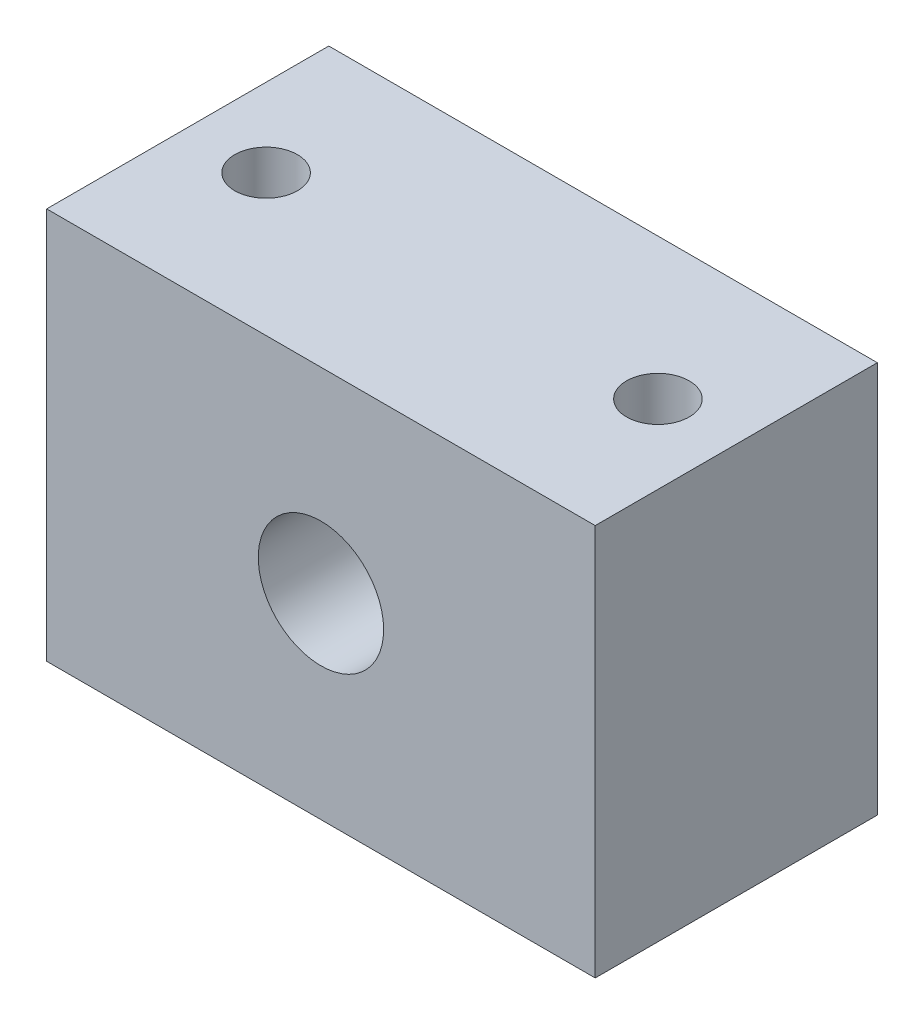
SolidWorks part; units mm, degrees
ref_plane "Front Plane" through (0, 0, 0) normal (0, 0, 1) x (1, 0, 0)
ref_plane "Top Plane" through (0, 0, 0) normal (0, 1, 0) x (1, 0, 0)
ref_plane "Right Plane" through (0, 0, 0) normal (1, 0, 0) x (0, 0, -1)
sketch "Sketch1" plane through (0, 0, 0) normal (0, 0, 1) x (1, 0, 0)
  line L1 (-17.5, 12.5) -> (17.5, 12.5)
  line L2 (-17.5, 12.5) -> (-17.5, -12.5)
  line L3 (-17.5, -12.5) -> (17.5, -12.5)
  line L4 (17.5, 12.5) -> (17.5, -12.5)
  line L5 (-17.5, 12.5) -> (17.5, -12.5) construction
  line L6 (-17.5, -12.5) -> (17.5, 12.5) construction
  circle A0 centre (0, 0) radius 4
  dimension "D1" = 8
  dimension "D2" = 25
  dimension "D3" = 35
extrude "Boss-Extrude1" add sketch "Sketch1" along normal blind 18
sketch "Sketch3" plane through (0, 12.5, 0) normal (0, 1, 0) x (1, 0, 0)
  line L0 (0, -1000) -> (0, 49000) construction
  line L1 (-1020, -9) -> (48980, -9) construction
  line L2 (-17.5, -18) -> (-17.5, 0) construction
  circle A0 centre (-12.5, -9) radius 2
  circle A1 centre (12.5, -9) radius 2
  point P8 (-17.5, -9)
  dimension "D2" = 4
  dimension "D1" = 5
extrude "Cut-Extrude1" cut sketch "Sketch3" against normal through all
